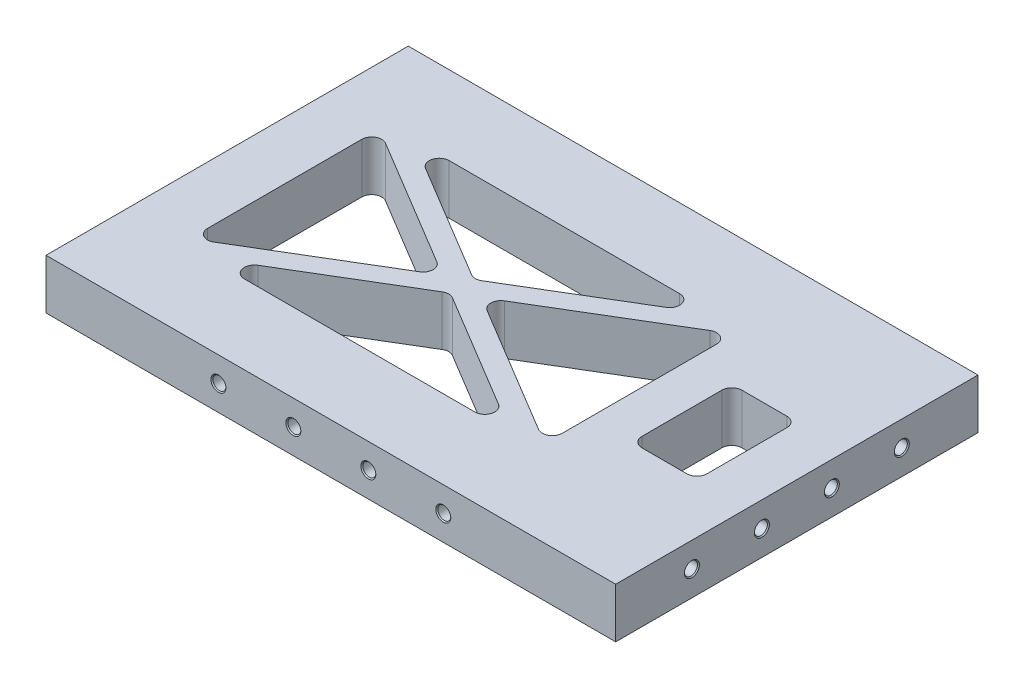
SolidWorks part; units mm, degrees
ref_plane "前基準面" through (0, 0, 0) normal (0, 0, 1) x (1, 0, 0)
ref_plane "上基準面" through (0, 0, 0) normal (0, 1, 0) x (1, 0, 0)
ref_plane "右基準面" through (0, 0, 0) normal (1, 0, 0) x (0, 0, -1)
sketch "草圖1" plane through (0, 0, 0) normal (0, 1, 0) x (1, 0, 0)
  line L1 (-57, 36.25) -> (57, 36.25)
  line L2 (-57, 36.25) -> (-57, -36.25)
  line L3 (-57, -36.25) -> (57, -36.25)
  line L4 (57, 36.25) -> (57, -36.25)
  line L5 (-57, 36.25) -> (57, -36.25) construction
  line L6 (-57, -36.25) -> (57, 36.25) construction
  point P0 (0, 0)
  dimension "D1" = 72.5
  dimension "D2" = 114
extrude "填料-伸長1" add sketch "草圖1" along normal blind 10
sketch "草圖2" plane through (0, 0, 36.25) normal (0, 0, 1) x (1, 0, 0)
  line L0 (-57, 10) -> (-57, 0) construction
  line L1 (-57, 0) -> (57, 0) construction
  circle A0 centre (-22.5, 5) radius 1.3
  dimension "D1" = 2.6
  dimension "D2" = 34.5
  dimension "D3" = 5
extrude "除料-伸長1" cut sketch "草圖2" against normal blind 8
pattern_linear "直線複製排列1" count 4 spacing 15 along (1, 0, 0) of "除料-伸長1"
mirror "鏡射1" about plane through (0, 0, 0) normal (0, 0, 1) of "除料-伸長1", "直線複製排列1"
sketch "草圖3" plane through (-57, 0, 0) normal (-1, 0, 0) x (0, 0, 1)
  line L0 (-36.25, 10) -> (36.25, 10) construction
  line L1 (-36.25, 10) -> (-36.25, 0) construction
  circle A0 centre (-21, 5) radius 1.3
  dimension "D1" = 2.6
  dimension "D2" = 5
  dimension "D3" = 15.25
extrude "除料-伸長2" cut sketch "草圖3" against normal blind 7.5
pattern_linear "直線複製排列2" count 4 spacing 14 along (0, 0, 1) of "除料-伸長2"
mirror "鏡射2" about plane through (0, 0, 0) normal (1, 0, 0) of "除料-伸長2", "直線複製排列2"
sketch "草圖4" plane through (0, 10, 0) normal (0, 1, 0) x (1, 0, 0)
  line L0 (57, -36.25) -> (57, 36.25) construction
  line L1 (34, 10) -> (47, 10)
  line L2 (34, 10) -> (34, -10)
  line L3 (34, -10) -> (47, -10)
  line L4 (47, 10) -> (47, -10)
  line L5 (34, 10) -> (47, -10) construction
  line L6 (34, -10) -> (47, 10) construction
  line L8 (-47.5, 22.5) -> (27.5, 22.5) construction
  line L9 (-47.5, 22.5) -> (-47.5, -22.5) construction
  line L10 (-47.5, -22.5) -> (27.5, -22.5) construction
  line L11 (27.5, 22.5) -> (27.5, -22.5) construction
  line L12 (-47.5, 22.5) -> (27.5, -22.5) construction
  line L13 (-47.5, -22.5) -> (27.5, 22.5) construction
  line L16 (-45.5, 18.9676) -> (-45.5, -18.9676)
  line L17 (-40.2794, -20.5) -> (20.2794, -20.5)
  line L18 (25.5, 18.9676) -> (25.5, -18.9676)
  line L21 (-40.2794, 20.5) -> (-10, 2.3324)
  line L22 (-6.1127, 0) -> (25.5, -18.9676)
  line L23 (-48.529, -20.785) -> (-47.5, -20.1676)
  line L24 (-46.471, 24.215) -> (28.529, -20.785) construction
  line L25 (-40.2794, 20.5) -> (20.2794, 20.5)
  line L26 (-45.5, 20.5) -> (25.5, 20.5) construction
  line L27 (-45.5, 20.5) -> (-45.5, -20.5) construction
  line L28 (-45.5, 18.9676) -> (-13.8873, 0)
  line L30 (-45.5, -18.9676) -> (-13.8873, 0)
  line L31 (-48.529, -20.785) -> (26.471, 24.215) construction
  line L32 (-45.5, -20.5) -> (25.5, -20.5) construction
  line L33 (-40.2794, -20.5) -> (-10, -2.3324)
  line L34 (25.5, 20.5) -> (25.5, -20.5) construction
  line L35 (-6.1127, 0) -> (25.5, 18.9676)
  line L36 (-10, -2.3324) -> (20.2794, -20.5)
  line L37 (-10, 2.3324) -> (20.2794, 20.5)
  point P0 (40.5, 0)
  point P7 (-10, 0)
  dimension "D1" = 20
  dimension "D2" = 13
  dimension "D3" = 10
  dimension "D4" = 10
  dimension "D5" = 75
  dimension "D6" = 45
  dimension "D7" = 2
  dimension "D10" = 2
  dimension "D12" = 2
  dimension "D8" = 2
  dimension "D9" = 2
  dimension "D11" = 2
extrude "除料-伸長3" cut sketch "草圖4" against normal up to next contours L16 L30 L28 | L21 L37 L25 | L35 L22 L18 | L36 L33 L17 | L4 L1 L2 L3
fillet "圓角1" radius 2 16 edges at (34, 5, 10) (34, 5, -10) (47, 5, -10) (47, 5, 10) (25.5, 5, 18.9676) (25.5, 5, -18.9676) (20.2794, 5, -20.5) (-40.2794, 5, -20.5) (-45.5, 5, -18.9676) (-45.5, 5, 18.9676) (-40.2794, 5, 20.5) (20.2794, 5, 20.5) (-10, 5, 2.3324) (-6.1127, 5, 0) (-10, 5, -2.3324) (-13.8873, 5, 0)
chamfer "導角1" distance 0.2 distance2 0.2 16 edges at (23.8, 5, 36.25) (8.8, 5, 36.25) (-6.2, 5, 36.25) (-21.2, 5, 36.25) (-57, 5, 22.3) (-57, 5, 8.3) (-57, 5, -5.7) (-57, 5, -19.7) (-21.2, 5, -36.25) (-6.2, 5, -36.25) (8.8, 5, -36.25) (23.8, 5, -36.25) (57, 5, -19.7) (57, 5, -5.7) (57, 5, 8.3) (57, 5, 22.3)
